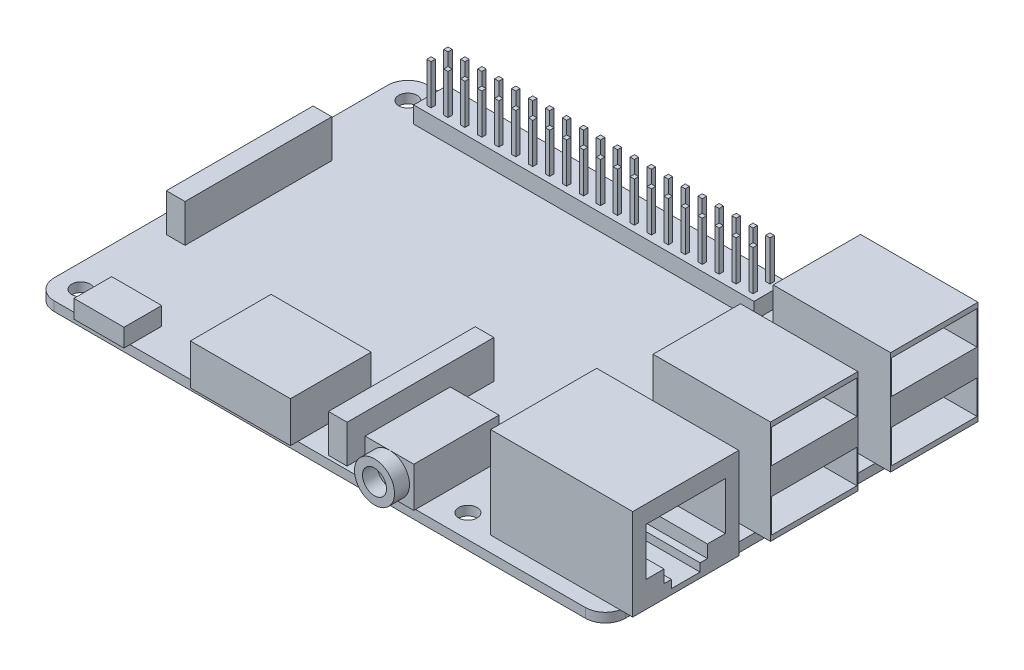
SolidWorks part; units mm, degrees
ref_plane "Front Plane" through (0, 0, 0) normal (0, 0, 1) x (1, 0, 0)
ref_plane "Top Plane" through (0, 0, 0) normal (0, 1, 0) x (1, 0, 0)
ref_plane "Right Plane" through (0, 0, 0) normal (1, 0, 0) x (0, 0, -1)
sketch "Sketch1" plane through (0, 0, 0) normal (0, 1, 0) x (1, 0, 0)
  line L1 (-39.8, -28) -> (39.8, -28)
  line L2 (-42.8, -25) -> (-42.8, 25)
  line L3 (-39.8, 28) -> (39.8, 28)
  line L4 (42.8, -25) -> (42.8, 25)
  line L5 (-42.8, -28) -> (42.8, 28) construction
  line L6 (-42.8, 28) -> (42.8, -28) construction
  arc A0 (-42.8, 25) -> (-39.8, 28) centre (-39.8, 25) cw
  arc A1 (-39.8, -28) -> (-42.8, -25) centre (-39.8, -25) cw
  arc A2 (39.8, -28) -> (42.8, -25) centre (39.8, -25) ccw
  arc A3 (39.8, 28) -> (42.8, 25) centre (39.8, 25) cw
  point P0 (0, 0)
  dimension "D3" = 3
  dimension "D1" = 56
  dimension "D2" = 85.6
extrude "Boss-Extrude1" add sketch "Sketch1" along normal blind 1.4
sketch "Sketch2" plane through (0, 1.4, 0) normal (0, 1, 0) x (1, 0, 0)
  line L0 (-42.8, 0) -> (0, 0) construction
  line L2 (-42.8, 25) -> (-42.8, -25) construction
  line L3 (39.8, 28) -> (-39.8, 28) construction
  circle A0 centre (-39.3, 24.5) radius 1.375
  circle A1 centre (-39.3, -24.5) radius 1.375
  circle A2 centre (18.7, 24.5) radius 1.375
  circle A3 centre (18.7, -24.5) radius 1.375
  dimension "D1" = 3.5
  dimension "D3" = 2.75
  dimension "D4" = 2.75
  dimension "D5" = 58
  dimension "D2" = 3.5
  dimension "D6" = 3.5
extrude "Cut-Extrude1" cut sketch "Sketch2" against normal through all
sketch "Sketch3" plane through (0, 1.4, 0) normal (0, 1, 0) x (1, 0, 0)
  line L5 (-39.8, -28) -> (39.8, -28) construction
  line L6 (-35.95, -28.9) -> (-28.45, -28.9)
  line L7 (-35.95, -28.9) -> (-35.95, -23.25)
  line L8 (-35.95, -23.25) -> (-28.45, -23.25)
  line L9 (-28.45, -28.9) -> (-28.45, -23.25)
  line L10 (-35.95, -28.9) -> (-28.45, -23.25) construction
  line L11 (-35.95, -23.25) -> (-28.45, -28.9) construction
  line L12 (-42.8, 25) -> (-42.8, -25) construction
  point P6 (-32.2, -26.075)
  dimension "D1" = 4.75
  dimension "D2" = 10.6
  dimension "D4" = 5.65
  dimension "D5" = 7.5
extrude "Boss-Extrude2" add sketch "Sketch3" along normal blind 2.7
sketch "Sketch4" plane through (0, 1.4, 0) normal (0, 1, 0) x (1, 0, 0)
  line L0 (-28.45, -28) -> (39.8, -28) construction
  line L1 (-18.3, -29.1) -> (-3.3, -29.1)
  line L2 (-18.3, -29.1) -> (-18.3, -17)
  line L3 (-18.3, -17) -> (-3.3, -17)
  line L4 (-3.3, -29.1) -> (-3.3, -17)
  line L5 (-18.3, -29.1) -> (-3.3, -17) construction
  line L6 (-18.3, -17) -> (-3.3, -29.1) construction
  line L7 (-42.8, 25) -> (-42.8, -25) construction
  point P0 (-10.8, -23.05)
  dimension "D1" = 12.1
  dimension "D2" = 15
  dimension "D3" = 11
  dimension "D4" = 32
extrude "Boss-Extrude3" add sketch "Sketch4" along normal blind 6.1
sketch "Sketch5" plane through (0, 1.4, 0) normal (0, 1, 0) x (1, 0, 0)
  line L1 (0.8, -27.5) -> (3.6, -27.5)
  line L2 (0.8, -27.5) -> (0.8, -5.5)
  line L3 (0.8, -5.5) -> (3.6, -5.5)
  line L4 (3.6, -27.5) -> (3.6, -5.5)
  line L5 (0.8, -27.5) -> (3.6, -5.5) construction
  line L6 (0.8, -5.5) -> (3.6, -27.5) construction
  line L7 (-3.3, -28) -> (39.8, -28) construction
  line L8 (-42.8, 25) -> (-42.8, -25) construction
  point P0 (2.2, -16.5)
  point P9 (0, 0)
  dimension "D1" = 11.5
  dimension "D2" = 45
  dimension "D3" = 22
  dimension "D4" = 2.8
extrude "Boss-Extrude4" add sketch "Sketch5" along normal blind 5.7
sketch "Sketch6" plane through (0, 1.4, 0) normal (0, 1, 0) x (1, 0, 0)
  line L0 (-42.8, 25) -> (-42.8, -25) construction
  line L1 (7.05, -15.5) -> (14.35, -15.5)
  line L2 (7.05, -15.5) -> (7.05, -28)
  line L3 (7.05, -28) -> (14.35, -28)
  line L4 (14.35, -15.5) -> (14.35, -28)
  line L5 (7.05, -15.5) -> (14.35, -28) construction
  line L6 (7.05, -28) -> (14.35, -15.5) construction
  line L7 (-3.3, -28) -> (39.8, -28) construction
  point P0 (10.7, -21.75)
  dimension "D1" = 53.5
  dimension "D2" = 12.5
  dimension "D3" = 7.3
extrude "Boss-Extrude5" add sketch "Sketch6" along normal blind 6 separate body
sketch "Sketch7" plane through (0, 0, 28) normal (0, 0, 1) x (1, 0, 0)
  line L1 (7.05, 1.4) -> (14.35, 7.4) construction
  line L3 (7.05, 7.4) -> (14.35, 1.4) construction
  circle A0 centre (10.7, 4.4) radius 3
  point P2 (0, 0)
  point P3 (10.7, 4.4)
  dimension "D1" = 6
extrude "Boss-Extrude6" add sketch "Sketch7" along normal blind 2.5
sketch "Sketch8" plane through (0, 1.4, 0) normal (0, 1, 0) x (1, 0, 0)
  line L0 (14.35, -28) -> (39.8, -28) construction
  line L1 (23.3, -25.7) -> (44.6, -25.7)
  line L2 (23.3, -25.7) -> (23.3, -9.8)
  line L3 (23.3, -9.8) -> (44.6, -9.8)
  line L4 (44.6, -25.7) -> (44.6, -9.8)
  line L5 (23.3, -25.7) -> (44.6, -9.8) construction
  line L6 (23.3, -9.8) -> (44.6, -25.7) construction
  line L7 (42.8, -25) -> (42.8, 25) construction
  point P0 (33.95, -17.75)
  dimension "D1" = 15.9
  dimension "D2" = 21.3
  dimension "D3" = 10.25
  dimension "D4" = 19.5
extrude "Boss-Extrude7" add sketch "Sketch8" along normal blind 13.7 separate body
sketch "Sketch9" plane through (0, 0, 30.5) normal (0, 0, 1) x (1, 0, 0)
  circle A0 centre (10.7, 4.4) radius 3 construction
  circle A1 centre (10.7, 4.4) radius 3
  circle A2 centre (10.7, 4.4) radius 1.8
  dimension "D1" = 3.6
extrude "Cut-Extrude3" cut sketch "Sketch9" against normal blind 13 contours A2
sketch "Sketch10" plane through (44.6, 0, 0) normal (1, 0, 0) x (0, 0, -1)
  line L0 (-15.6, 2.2) -> (-19.9, 2.2)
  line L2 (-15.6, 2.2) -> (-15.6, 3.4)
  line L3 (-15.6, 3.4) -> (-14.5, 3.4)
  line L4 (-25.7, 1.4) -> (-9.8, 1.4) construction
  line L5 (-17.75, 1.4) -> (-17.75, 15.1) construction
  line L6 (-25.7, 15.1) -> (-9.8, 15.1) construction
  line L7 (-25, 1.4) -> (25, 1.4) construction
  line L8 (-9.8, 15.1) -> (-9.8, 1.4) construction
  line L9 (-14.5, 3.4) -> (-14.5, 5.3)
  line L10 (-14.5, 5.3) -> (-11.8, 5.3)
  line L11 (-11.8, 5.3) -> (-11.8, 12.45)
  line L12 (-11.8, 12.45) -> (-23.7, 12.45)
  line L13 (-23.7, 5.3) -> (-23.7, 12.45)
  line L14 (-21, 5.3) -> (-23.7, 5.3)
  line L15 (-21, 3.4) -> (-21, 5.3)
  line L16 (-19.9, 3.4) -> (-21, 3.4)
  line L17 (-19.9, 2.2) -> (-19.9, 3.4)
  point P19 (-17.75, 2.2)
  point P20 (-17.75, 12.45)
  dimension "D1" = 0.8
  dimension "D2" = 2
  dimension "D3" = 5.8
  dimension "D4" = 4.7
  dimension "D5" = 2
  dimension "D6" = 3.9
  dimension "D7" = 2.65
extrude "Cut-Extrude4" cut sketch "Sketch10" against normal blind 9.7
sketch "Sketch11" plane through (0, 1.4, 0) normal (0, 1, 0) x (1, 0, 0)
  line L0 (42.8, 10) -> (-42.8, 10) construction
  line L1 (42.8, -25) -> (42.8, 25) construction
  line L2 (-42.8, 25) -> (-42.8, -25) construction
  line L3 (14.35, -28) -> (39.8, -28) construction
  line L4 (27.5, -5.55) -> (45.1, -5.55)
  line L5 (27.5, -5.55) -> (27.5, 7.55)
  line L6 (27.5, 7.55) -> (45.1, 7.55)
  line L7 (45.1, -5.55) -> (45.1, 7.55)
  line L8 (27.5, -5.55) -> (45.1, 7.55) construction
  line L9 (27.5, 7.55) -> (45.1, -5.55) construction
  line L10 (45.1, 25.55) -> (45.1, 12.45)
  line L11 (27.5, 25.55) -> (45.1, 25.55)
  line L12 (27.5, 25.55) -> (27.5, 12.45)
  line L13 (27.5, 25.55) -> (45.1, 12.45) construction
  line L14 (27.5, 12.45) -> (45.1, 25.55) construction
  line L15 (27.5, 12.45) -> (45.1, 12.45)
  point P6 (36.3, 1)
  point P17 (36.3, 19)
  dimension "D1" = 29
  dimension "D2" = 47
  dimension "D3" = 13.1
  dimension "D4" = 17.6
  dimension "D5" = 15.3
extrude "Boss-Extrude8" add sketch "Sketch11" along normal blind 15.5
sketch "Sketch12" plane through (45.1, 0, 0) normal (1, 0, 0) x (0, 0, -1)
  line L0 (10, 1.4) -> (10, 16.8274) construction
  line L1 (7.55, 1.4) -> (12.45, 1.4) construction
  line L2 (-5.55, 9.15) -> (7.55, 9.15) construction
  line L3 (-5.4, 11.15) -> (7.4, 11.15)
  line L4 (-5.4, 11.15) -> (-5.4, 16.15)
  line L5 (-5.4, 16.15) -> (7.4, 16.15)
  line L6 (7.4, 11.15) -> (7.4, 16.15)
  line L7 (-5.4, 11.15) -> (7.4, 16.15) construction
  line L8 (-5.4, 16.15) -> (7.4, 11.15) construction
  line L13 (-5.55, 16.9) -> (-5.55, 1.4) construction
  line L14 (7.55, 16.9) -> (7.55, 1.4) construction
  line L15 (-5.4, 2.15) -> (7.4, 7.15) construction
  line L20 (-5.4, 7.15) -> (7.4, 2.15) construction
  line L21 (7.4, 7.15) -> (7.4, 2.15)
  line L26 (1, 1.4) -> (1, 16.9) construction
  line L27 (-5.55, 1.4) -> (7.55, 1.4) construction
  line L28 (-5.55, 16.9) -> (7.55, 16.9) construction
  line L29 (-5.4, 2.15) -> (7.4, 2.15)
  line L30 (-5.4, 7.15) -> (-5.4, 2.15)
  line L31 (-5.4, 7.15) -> (7.4, 7.15)
  line L32 (25.4, 7.15) -> (12.6, 2.15) construction
  line L33 (25.4, 2.15) -> (12.6, 7.15) construction
  line L34 (25.4, 16.15) -> (12.6, 11.15) construction
  line L35 (25.4, 11.15) -> (12.6, 16.15) construction
  line L36 (25.4, 7.15) -> (12.6, 7.15)
  line L37 (25.4, 7.15) -> (25.4, 2.15)
  line L38 (25.4, 2.15) -> (12.6, 2.15)
  line L39 (12.6, 7.15) -> (12.6, 2.15)
  line L40 (12.6, 11.15) -> (12.6, 16.15)
  line L41 (25.4, 16.15) -> (12.6, 16.15)
  line L42 (25.4, 11.15) -> (25.4, 16.15)
  line L43 (25.4, 11.15) -> (12.6, 11.15)
  point P4 (1, 13.65)
  point P19 (1, 4.65)
  point P34 (19, 4.65)
  point P35 (19, 13.65)
  dimension "D1" = 12.8
  dimension "D2" = 5
  dimension "D3" = 4
extrude "Cut-Extrude5" cut sketch "Sketch12" against normal blind 9
sketch "Sketch13" plane through (0, 1.4, 0) normal (0, 1, 0) x (1, 0, 0)
  line L0 (-39.8, -28) -> (-35.95, -28) construction
  line L1 (-40, -11) -> (-37.2, -11)
  line L2 (-40, -11) -> (-40, 11)
  line L3 (-40, 11) -> (-37.2, 11)
  line L4 (-37.2, -11) -> (-37.2, 11)
  line L5 (-40, -11) -> (-37.2, 11) construction
  line L6 (-40, 11) -> (-37.2, -11) construction
  line L7 (-42.8, 25) -> (-42.8, -25) construction
  point P0 (-38.6, 0)
  dimension "D1" = 28
  dimension "D2" = 22
  dimension "D3" = 2.8
  dimension "D4" = 5.6
extrude "Boss-Extrude9" add sketch "Sketch13" along normal blind 5.7
sketch "Sketch14" plane through (0, 1.4, 0) normal (0, 1, 0) x (1, 0, 0)
  line L1 (-35.8, 21.8741) -> (15.2, 21.8741)
  line L2 (-35.8, 21.8741) -> (-35.8, 26.8741)
  line L3 (-35.8, 26.8741) -> (15.2, 26.8741)
  line L4 (15.2, 21.8741) -> (15.2, 26.8741)
  line L5 (-35.8, 21.8741) -> (15.2, 26.8741) construction
  line L6 (-35.8, 26.8741) -> (15.2, 21.8741) construction
  circle A0 centre (-39.3, 24.5) radius 1.375 construction
  circle A1 centre (-39.3, 24.5) radius 1.375
  point P0 (-10.3, 24.3741)
  dimension "D1" = 5
  dimension "D2" = 51
  dimension "D3" = 29
extrude "Boss-Extrude10" add sketch "Sketch14" along normal blind 2.5 contours L2 L1 L4 L3
sketch "Sketch15" plane through (0, 3.9, 0) normal (0, 1, 0) x (1, 0, 0)
  line L0 (-35.8, 24.3741) -> (15.2, 24.3741) construction
  line L1 (-35.8, 26.8741) -> (-35.8, 21.8741) construction
  line L2 (15.2, 21.8741) -> (15.2, 26.8741) construction
  line L3 (-31.57, 25.3241) -> (-32.21, 25.3241)
  line L4 (-34.11, 25.3241) -> (-34.75, 25.3241)
  line L5 (-34.11, 25.3241) -> (-34.11, 25.9641)
  line L6 (-34.11, 25.9641) -> (-34.75, 25.9641)
  line L7 (-34.75, 25.3241) -> (-34.75, 25.9641)
  line L8 (-34.11, 25.3241) -> (-34.75, 25.9641) construction
  line L9 (-34.11, 25.9641) -> (-34.75, 25.3241) construction
  line L10 (-31.57, 25.3241) -> (-31.57, 25.9641)
  line L11 (-31.57, 25.9641) -> (-32.21, 25.9641)
  line L12 (-32.21, 25.3241) -> (-32.21, 25.9641)
  line L13 (-31.57, 25.3241) -> (-32.21, 25.9641) construction
  line L14 (-31.57, 25.9641) -> (-32.21, 25.3241) construction
  line L15 (-29.03, 25.3241) -> (-29.67, 25.3241)
  line L16 (-29.03, 25.3241) -> (-29.03, 25.9641)
  line L17 (-29.03, 25.9641) -> (-29.67, 25.9641)
  line L18 (-29.67, 25.3241) -> (-29.67, 25.9641)
  line L19 (-29.03, 25.3241) -> (-29.67, 25.9641) construction
  line L20 (-29.03, 25.9641) -> (-29.67, 25.3241) construction
  line L21 (-26.49, 25.3241) -> (-27.13, 25.3241)
  line L22 (-26.49, 25.3241) -> (-26.49, 25.9641)
  line L23 (-26.49, 25.9641) -> (-27.13, 25.9641)
  line L24 (-27.13, 25.3241) -> (-27.13, 25.9641)
  line L25 (-26.49, 25.3241) -> (-27.13, 25.9641) construction
  line L26 (-26.49, 25.9641) -> (-27.13, 25.3241) construction
  line L27 (-23.95, 25.3241) -> (-24.59, 25.3241)
  line L28 (-23.95, 25.3241) -> (-23.95, 25.9641)
  line L29 (-23.95, 25.9641) -> (-24.59, 25.9641)
  line L30 (-24.59, 25.3241) -> (-24.59, 25.9641)
  line L31 (-23.95, 25.3241) -> (-24.59, 25.9641) construction
  line L32 (-23.95, 25.9641) -> (-24.59, 25.3241) construction
  line L33 (-21.41, 25.3241) -> (-22.05, 25.3241)
  line L34 (-21.41, 25.3241) -> (-21.41, 25.9641)
  line L35 (-21.41, 25.9641) -> (-22.05, 25.9641)
  line L36 (-22.05, 25.3241) -> (-22.05, 25.9641)
  line L37 (-21.41, 25.3241) -> (-22.05, 25.9641) construction
  line L38 (-21.41, 25.9641) -> (-22.05, 25.3241) construction
  line L39 (-18.87, 25.3241) -> (-19.51, 25.3241)
  line L40 (-18.87, 25.3241) -> (-18.87, 25.9641)
  line L41 (-18.87, 25.9641) -> (-19.51, 25.9641)
  line L42 (-19.51, 25.3241) -> (-19.51, 25.9641)
  line L43 (-18.87, 25.3241) -> (-19.51, 25.9641) construction
  line L44 (-18.87, 25.9641) -> (-19.51, 25.3241) construction
  line L45 (-16.33, 25.3241) -> (-16.97, 25.3241)
  line L46 (-16.33, 25.3241) -> (-16.33, 25.9641)
  line L47 (-16.33, 25.9641) -> (-16.97, 25.9641)
  line L48 (-16.97, 25.3241) -> (-16.97, 25.9641)
  line L49 (-16.33, 25.3241) -> (-16.97, 25.9641) construction
  line L50 (-16.33, 25.9641) -> (-16.97, 25.3241) construction
  line L51 (-13.79, 25.3241) -> (-14.43, 25.3241)
  line L52 (-13.79, 25.3241) -> (-13.79, 25.9641)
  line L53 (-13.79, 25.9641) -> (-14.43, 25.9641)
  line L54 (-14.43, 25.3241) -> (-14.43, 25.9641)
  line L55 (-13.79, 25.3241) -> (-14.43, 25.9641) construction
  line L56 (-13.79, 25.9641) -> (-14.43, 25.3241) construction
  line L57 (-11.25, 25.3241) -> (-11.89, 25.3241)
  line L58 (-11.25, 25.3241) -> (-11.25, 25.9641)
  line L59 (-11.25, 25.9641) -> (-11.89, 25.9641)
  line L60 (-11.89, 25.3241) -> (-11.89, 25.9641)
  line L61 (-11.25, 25.3241) -> (-11.89, 25.9641) construction
  line L62 (-11.25, 25.9641) -> (-11.89, 25.3241) construction
  line L63 (-10.3, 21.8741) -> (-10.3, 26.8741) construction
  line L64 (-35.8, 21.8741) -> (15.2, 21.8741) construction
  line L65 (15.2, 26.8741) -> (-35.8, 26.8741) construction
  line L66 (-11.25, 22.7841) -> (-11.89, 23.4241) construction
  line L67 (-11.25, 23.4241) -> (-11.89, 22.7841) construction
  line L68 (-13.79, 22.7841) -> (-14.43, 23.4241) construction
  line L69 (-13.79, 23.4241) -> (-14.43, 22.7841) construction
  line L70 (-16.33, 22.7841) -> (-16.97, 23.4241) construction
  line L71 (-16.33, 23.4241) -> (-16.97, 22.7841) construction
  line L72 (-18.87, 22.7841) -> (-19.51, 23.4241) construction
  line L73 (-18.87, 23.4241) -> (-19.51, 22.7841) construction
  line L74 (-21.41, 22.7841) -> (-22.05, 23.4241) construction
  line L75 (-21.41, 23.4241) -> (-22.05, 22.7841) construction
  line L76 (-23.95, 22.7841) -> (-24.59, 23.4241) construction
  line L77 (-23.95, 23.4241) -> (-24.59, 22.7841) construction
  line L78 (-26.49, 22.7841) -> (-27.13, 23.4241) construction
  line L79 (-26.49, 23.4241) -> (-27.13, 22.7841) construction
  line L80 (-29.03, 22.7841) -> (-29.67, 23.4241) construction
  line L81 (-29.03, 23.4241) -> (-29.67, 22.7841) construction
  line L82 (-31.57, 22.7841) -> (-32.21, 23.4241) construction
  line L83 (-31.57, 23.4241) -> (-32.21, 22.7841) construction
  line L84 (-34.11, 22.7841) -> (-34.75, 23.4241) construction
  line L85 (-34.11, 23.4241) -> (-34.75, 22.7841) construction
  line L86 (-11.89, 23.4241) -> (-11.89, 22.7841)
  line L87 (-11.25, 22.7841) -> (-11.89, 22.7841)
  line L88 (-11.25, 23.4241) -> (-11.25, 22.7841)
  line L89 (-11.25, 23.4241) -> (-11.89, 23.4241)
  line L90 (-14.43, 23.4241) -> (-14.43, 22.7841)
  line L91 (-13.79, 22.7841) -> (-14.43, 22.7841)
  line L92 (-13.79, 23.4241) -> (-13.79, 22.7841)
  line L93 (-13.79, 23.4241) -> (-14.43, 23.4241)
  line L94 (-16.97, 23.4241) -> (-16.97, 22.7841)
  line L95 (-16.33, 22.7841) -> (-16.97, 22.7841)
  line L96 (-16.33, 23.4241) -> (-16.33, 22.7841)
  line L97 (-16.33, 23.4241) -> (-16.97, 23.4241)
  line L98 (-19.51, 23.4241) -> (-19.51, 22.7841)
  line L99 (-18.87, 22.7841) -> (-19.51, 22.7841)
  line L100 (-18.87, 23.4241) -> (-18.87, 22.7841)
  line L101 (-18.87, 23.4241) -> (-19.51, 23.4241)
  line L102 (-22.05, 23.4241) -> (-22.05, 22.7841)
  line L103 (-21.41, 22.7841) -> (-22.05, 22.7841)
  line L104 (-21.41, 23.4241) -> (-21.41, 22.7841)
  line L105 (-21.41, 23.4241) -> (-22.05, 23.4241)
  line L106 (-24.59, 23.4241) -> (-24.59, 22.7841)
  line L107 (-23.95, 22.7841) -> (-24.59, 22.7841)
  line L108 (-23.95, 23.4241) -> (-23.95, 22.7841)
  line L109 (-23.95, 23.4241) -> (-24.59, 23.4241)
  line L110 (-27.13, 23.4241) -> (-27.13, 22.7841)
  line L111 (-26.49, 22.7841) -> (-27.13, 22.7841)
  line L112 (-26.49, 23.4241) -> (-26.49, 22.7841)
  line L113 (-26.49, 23.4241) -> (-27.13, 23.4241)
  line L114 (-29.67, 23.4241) -> (-29.67, 22.7841)
  line L115 (-29.03, 22.7841) -> (-29.67, 22.7841)
  line L116 (-29.03, 23.4241) -> (-29.03, 22.7841)
  line L117 (-29.03, 23.4241) -> (-29.67, 23.4241)
  line L118 (-32.21, 23.4241) -> (-32.21, 22.7841)
  line L119 (-31.57, 22.7841) -> (-32.21, 22.7841)
  line L120 (-31.57, 23.4241) -> (-31.57, 22.7841)
  line L121 (-34.75, 23.4241) -> (-34.75, 22.7841)
  line L122 (-34.11, 22.7841) -> (-34.75, 22.7841)
  line L123 (-34.11, 23.4241) -> (-34.11, 22.7841)
  line L124 (-34.11, 23.4241) -> (-34.75, 23.4241)
  line L125 (-31.57, 23.4241) -> (-32.21, 23.4241)
  line L126 (13.51, 23.4241) -> (14.15, 22.7841) construction
  line L127 (13.51, 22.7841) -> (14.15, 23.4241) construction
  line L128 (10.97, 23.4241) -> (11.61, 22.7841) construction
  line L129 (10.97, 22.7841) -> (11.61, 23.4241) construction
  line L130 (8.43, 23.4241) -> (9.07, 22.7841) construction
  line L131 (8.43, 22.7841) -> (9.07, 23.4241) construction
  line L132 (5.89, 23.4241) -> (6.53, 22.7841) construction
  line L133 (5.89, 22.7841) -> (6.53, 23.4241) construction
  line L134 (3.35, 23.4241) -> (3.99, 22.7841) construction
  line L135 (3.35, 22.7841) -> (3.99, 23.4241) construction
  line L136 (0.81, 23.4241) -> (1.45, 22.7841) construction
  line L137 (0.81, 22.7841) -> (1.45, 23.4241) construction
  line L138 (-1.73, 23.4241) -> (-1.09, 22.7841) construction
  line L139 (-1.73, 22.7841) -> (-1.09, 23.4241) construction
  line L140 (-4.27, 23.4241) -> (-3.63, 22.7841) construction
  line L141 (-4.27, 22.7841) -> (-3.63, 23.4241) construction
  line L142 (-6.81, 23.4241) -> (-6.17, 22.7841) construction
  line L143 (-6.81, 22.7841) -> (-6.17, 23.4241) construction
  line L144 (-9.35, 23.4241) -> (-8.71, 22.7841) construction
  line L145 (-9.35, 22.7841) -> (-8.71, 23.4241) construction
  line L146 (-9.35, 25.9641) -> (-8.71, 25.3241) construction
  line L147 (-9.35, 25.3241) -> (-8.71, 25.9641) construction
  line L148 (-6.81, 25.9641) -> (-6.17, 25.3241) construction
  line L149 (-6.81, 25.3241) -> (-6.17, 25.9641) construction
  line L150 (-4.27, 25.9641) -> (-3.63, 25.3241) construction
  line L151 (-4.27, 25.3241) -> (-3.63, 25.9641) construction
  line L152 (-1.73, 25.9641) -> (-1.09, 25.3241) construction
  line L153 (-1.73, 25.3241) -> (-1.09, 25.9641) construction
  line L154 (0.81, 25.9641) -> (1.45, 25.3241) construction
  line L155 (0.81, 25.3241) -> (1.45, 25.9641) construction
  line L156 (3.35, 25.9641) -> (3.99, 25.3241) construction
  line L157 (3.35, 25.3241) -> (3.99, 25.9641) construction
  line L158 (5.89, 25.9641) -> (6.53, 25.3241) construction
  line L159 (5.89, 25.3241) -> (6.53, 25.9641) construction
  line L160 (8.43, 25.9641) -> (9.07, 25.3241) construction
  line L161 (8.43, 25.3241) -> (9.07, 25.9641) construction
  line L162 (10.97, 25.9641) -> (11.61, 25.3241) construction
  line L163 (10.97, 25.3241) -> (11.61, 25.9641) construction
  line L164 (13.51, 25.9641) -> (14.15, 25.3241) construction
  line L165 (13.51, 25.3241) -> (14.15, 25.9641) construction
  line L166 (10.97, 23.4241) -> (11.61, 23.4241)
  line L167 (13.51, 23.4241) -> (14.15, 23.4241)
  line L168 (13.51, 23.4241) -> (13.51, 22.7841)
  line L169 (13.51, 22.7841) -> (14.15, 22.7841)
  line L170 (14.15, 23.4241) -> (14.15, 22.7841)
  line L171 (10.97, 23.4241) -> (10.97, 22.7841)
  line L172 (10.97, 22.7841) -> (11.61, 22.7841)
  line L173 (11.61, 23.4241) -> (11.61, 22.7841)
  line L174 (8.43, 23.4241) -> (9.07, 23.4241)
  line L175 (8.43, 23.4241) -> (8.43, 22.7841)
  line L176 (8.43, 22.7841) -> (9.07, 22.7841)
  line L177 (9.07, 23.4241) -> (9.07, 22.7841)
  line L178 (5.89, 23.4241) -> (6.53, 23.4241)
  line L179 (5.89, 23.4241) -> (5.89, 22.7841)
  line L180 (5.89, 22.7841) -> (6.53, 22.7841)
  line L181 (6.53, 23.4241) -> (6.53, 22.7841)
  line L182 (3.35, 23.4241) -> (3.99, 23.4241)
  line L183 (3.35, 23.4241) -> (3.35, 22.7841)
  line L184 (3.35, 22.7841) -> (3.99, 22.7841)
  line L185 (3.99, 23.4241) -> (3.99, 22.7841)
  line L186 (0.81, 23.4241) -> (1.45, 23.4241)
  line L187 (0.81, 23.4241) -> (0.81, 22.7841)
  line L188 (0.81, 22.7841) -> (1.45, 22.7841)
  line L189 (1.45, 23.4241) -> (1.45, 22.7841)
  line L190 (-1.73, 23.4241) -> (-1.09, 23.4241)
  line L191 (-1.73, 23.4241) -> (-1.73, 22.7841)
  line L192 (-1.73, 22.7841) -> (-1.09, 22.7841)
  line L193 (-1.09, 23.4241) -> (-1.09, 22.7841)
  line L194 (-4.27, 23.4241) -> (-3.63, 23.4241)
  line L195 (-4.27, 23.4241) -> (-4.27, 22.7841)
  line L196 (-4.27, 22.7841) -> (-3.63, 22.7841)
  line L197 (-3.63, 23.4241) -> (-3.63, 22.7841)
  line L198 (-6.81, 23.4241) -> (-6.17, 23.4241)
  line L199 (-6.81, 23.4241) -> (-6.81, 22.7841)
  line L200 (-6.81, 22.7841) -> (-6.17, 22.7841)
  line L201 (-6.17, 23.4241) -> (-6.17, 22.7841)
  line L202 (-9.35, 23.4241) -> (-8.71, 23.4241)
  line L203 (-9.35, 23.4241) -> (-9.35, 22.7841)
  line L204 (-9.35, 22.7841) -> (-8.71, 22.7841)
  line L205 (-8.71, 23.4241) -> (-8.71, 22.7841)
  line L206 (-8.71, 25.3241) -> (-8.71, 25.9641)
  line L207 (-9.35, 25.9641) -> (-8.71, 25.9641)
  line L208 (-9.35, 25.3241) -> (-9.35, 25.9641)
  line L209 (-9.35, 25.3241) -> (-8.71, 25.3241)
  line L210 (-6.17, 25.3241) -> (-6.17, 25.9641)
  line L211 (-6.81, 25.9641) -> (-6.17, 25.9641)
  line L212 (-6.81, 25.3241) -> (-6.81, 25.9641)
  line L213 (-6.81, 25.3241) -> (-6.17, 25.3241)
  line L214 (-3.63, 25.3241) -> (-3.63, 25.9641)
  line L215 (-4.27, 25.9641) -> (-3.63, 25.9641)
  line L216 (-4.27, 25.3241) -> (-4.27, 25.9641)
  line L217 (-4.27, 25.3241) -> (-3.63, 25.3241)
  line L218 (-1.09, 25.3241) -> (-1.09, 25.9641)
  line L219 (-1.73, 25.9641) -> (-1.09, 25.9641)
  line L220 (-1.73, 25.3241) -> (-1.73, 25.9641)
  line L221 (-1.73, 25.3241) -> (-1.09, 25.3241)
  line L222 (1.45, 25.3241) -> (1.45, 25.9641)
  line L223 (0.81, 25.9641) -> (1.45, 25.9641)
  line L224 (0.81, 25.3241) -> (0.81, 25.9641)
  line L225 (0.81, 25.3241) -> (1.45, 25.3241)
  line L226 (3.99, 25.3241) -> (3.99, 25.9641)
  line L227 (3.35, 25.9641) -> (3.99, 25.9641)
  line L228 (3.35, 25.3241) -> (3.35, 25.9641)
  line L229 (3.35, 25.3241) -> (3.99, 25.3241)
  line L230 (6.53, 25.3241) -> (6.53, 25.9641)
  line L231 (5.89, 25.9641) -> (6.53, 25.9641)
  line L232 (5.89, 25.3241) -> (5.89, 25.9641)
  line L233 (5.89, 25.3241) -> (6.53, 25.3241)
  line L234 (9.07, 25.3241) -> (9.07, 25.9641)
  line L235 (8.43, 25.9641) -> (9.07, 25.9641)
  line L236 (8.43, 25.3241) -> (8.43, 25.9641)
  line L237 (8.43, 25.3241) -> (9.07, 25.3241)
  line L238 (11.61, 25.3241) -> (11.61, 25.9641)
  line L239 (10.97, 25.9641) -> (11.61, 25.9641)
  line L240 (10.97, 25.3241) -> (10.97, 25.9641)
  line L241 (14.15, 25.3241) -> (14.15, 25.9641)
  line L242 (13.51, 25.9641) -> (14.15, 25.9641)
  line L243 (13.51, 25.3241) -> (13.51, 25.9641)
  line L244 (13.51, 25.3241) -> (14.15, 25.3241)
  line L245 (10.97, 25.3241) -> (11.61, 25.3241)
  point P6 (-34.43, 25.6441)
  point P12 (-31.89, 25.6441)
  point P17 (-29.35, 25.6441)
  point P22 (-26.81, 25.6441)
  point P27 (-24.27, 25.6441)
  point P32 (-21.73, 25.6441)
  point P37 (-19.19, 25.6441)
  point P42 (-16.65, 25.6441)
  point P47 (-14.11, 25.6441)
  point P52 (-11.57, 25.6441)
  point P102 (-11.57, 23.1041)
  point P103 (-14.11, 23.1041)
  point P104 (-16.65, 23.1041)
  point P105 (-19.19, 23.1041)
  point P106 (-21.73, 23.1041)
  point P107 (-24.27, 23.1041)
  point P108 (-26.81, 23.1041)
  point P109 (-29.35, 23.1041)
  point P110 (-31.89, 23.1041)
  point P111 (-34.43, 23.1041)
  point P192 (13.83, 23.1041)
  point P193 (11.29, 23.1041)
  point P194 (8.75, 23.1041)
  point P195 (6.21, 23.1041)
  point P196 (3.67, 23.1041)
  point P197 (1.13, 23.1041)
  point P198 (-1.41, 23.1041)
  point P199 (-3.95, 23.1041)
  point P200 (-6.49, 23.1041)
  point P201 (-9.03, 23.1041)
  point P202 (-9.03, 25.6441)
  point P203 (-6.49, 25.6441)
  point P204 (-3.95, 25.6441)
  point P205 (-1.41, 25.6441)
  point P206 (1.13, 25.6441)
  point P207 (3.67, 25.6441)
  point P208 (6.21, 25.6441)
  point P209 (8.75, 25.6441)
  point P210 (11.29, 25.6441)
  point P211 (13.83, 25.6441)
  dimension "D1" = 0.64
  dimension "D2" = 10
  dimension "D3" = 2.54
  dimension "D4" = 2.54
extrude "Boss-Extrude11" add sketch "Sketch15" along normal blind 6
combine bodies "Combine1" operation type add bodies to combine 116 110
sketch "Sketch17" plane through (0, 0, 28) normal (0, 0, 1) x (1, 0, 0)
  line L0 (14.35, 7.4) -> (14.35, 1.4) construction
  line L1 (10.7, 7.4) -> (14.35, 7.4) construction
  line L2 (7.05, 7.4) -> (10.7, 7.4) construction
  line L3 (7.05, 7.4) -> (7.05, 1.4) construction
  line L4 (14.35, 7.4) -> (14.35, 1.4)
  line L5 (10.7, 7.4) -> (14.35, 7.4)
  line L6 (7.05, 7.4) -> (10.7, 7.4)
  line L7 (7.05, 7.4) -> (7.05, 1.4)
  line L8 (7.05, 1.4) -> (14.35, 1.4)
extrude "Boss-Extrude12" add sketch "Sketch17" along normal blind 0.253
